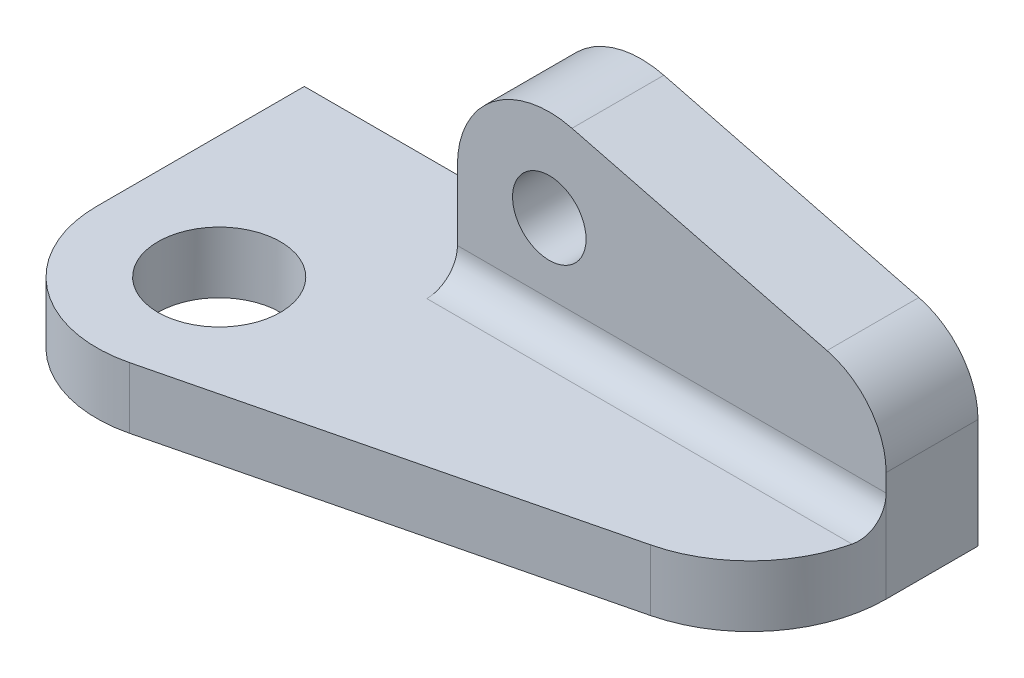
SolidWorks part; units mm, degrees
ref_plane "정면" through (0, 0, 0) normal (0, 0, 1) x (1, 0, 0)
ref_plane "윗면" through (0, 0, 0) normal (0, 1, 0) x (1, 0, 0)
ref_plane "우측면" through (0, 0, 0) normal (1, 0, 0) x (0, 0, -1)
sketch "Sketch2" plane through (0, 0, 0) normal (0, 1, 0) x (1, 0, 0)
  line L0 (0, 0) -> (110, 0)
  line L1 (110, 0) -> (110, -15)
  line L2 (93.0967, -36.5535) -> (24.7671, -53.3236)
  line L3 (0, -33.9) -> (0, 0)
  arc A0 (110, -15) -> (93.0967, -36.5535) centre (87.8068, -15) cw
  arc A1 (24.7671, -53.3236) -> (0, -33.9) centre (20, -33.9) cw
  point P9 (94.5015, -35.0764)
  point P10 (0, 0)
  point P11 (0, 0)
  point P12 (0, 0)
  point P13 (0, 0)
  point P14 (93.0967, -36.5535)
  dimension "D3" = 20
  dimension "D1" = 15
  dimension "D2" = 33.9
  dimension "D4" = 110
extrude "Boss-Extrude1" add sketch "Sketch2" along normal blind 10
sketch "Sketch4" plane through (0, 0, 0) normal (0, 0, -1) x (-1, 0, 0)
  line L0 (-110, 10) -> (-40, 10)
  line L1 (-110, 10) -> (0, 10) construction
  line L2 (-40, 10) -> (-40, 26.4)
  line L3 (-58.7043, 40.9354) -> (-100.3459, 30.3231)
  line L4 (-110, 17.9) -> (-110, 10)
  line L5 (-110, 0) -> (0, 0) construction
  arc A0 (-40, 26.4) -> (-58.7043, 40.9354) centre (-55, 26.4) ccw
  arc A1 (-100.3459, 30.3231) -> (-110, 17.9) centre (-97.1799, 17.9) ccw
  point P13 (-101.9718, 26.4)
  point P14 (-50.5348, 36.9348)
  point P15 (-101.9718, 28.6746)
  point P16 (-59.8434, 40.5965)
  point P17 (-101.6019, 28.5514)
  point P18 (-100.3459, 30.3231)
  dimension "D4" = 15
  dimension "D1" = 17.9
  dimension "D2" = 70
  dimension "D3" = 26.4
extrude "Boss-Extrude2" add sketch "Sketch4" against normal blind 15 contours L3 A1 L4 L0 L2 A0
hole_wizard "Ø20.0 (20) Diameter Hole1" positions "3DSketch1" profile "Sketch5" hole size "Ø20.0" standard "Ansi Metric" end condition up to next
sketch3d "3DSketch1"
  line L0 (20, 10, 33.9) -> (20, 0, 33.9) construction
  point P0 (20, 10, 33.9)
sketch "Sketch5" plane through (20, 10, 33.9) normal (1, 0, 0) x (0, 0, 1)
  line L0 (0, 0) -> (0, 10)
  line L1 (0, 10) -> (10, 10)
  line L2 (10, 10) -> (10, 0)
  line L5 (10, 0) -> (0, 0)
  line L11 (0, -6.35) -> (0, 107.95) construction
  dimension "관통 구멍 지름" = 20
  dimension "관통 구멍 깊이" = 10
hole_wizard "Ø12.0 (12) Diameter Hole1" positions "3DSketch2" profile "Sketch6" hole size "Ø12.0" standard "Ansi Metric" end condition up to next
sketch3d "3DSketch2"
  line L0 (55, 26.4, 15) -> (55, 26.4, 0) construction
  point P0 (55, 26.4, 15)
sketch "Sketch6" plane through (55, 26.4, 15) normal (1, 0, 0) x (0, -1, 0)
  line L0 (0, 0) -> (0, 15)
  line L1 (0, 15) -> (6, 15)
  line L2 (6, 15) -> (6, 0)
  line L5 (6, 0) -> (0, 0)
  line L11 (0, -6.35) -> (0, 107.95) construction
  dimension "관통 구멍 지름" = 12
  dimension "관통 구멍 깊이" = 15
fillet "Fillet1" radius 5 1 edges at (75, 10, 15)
